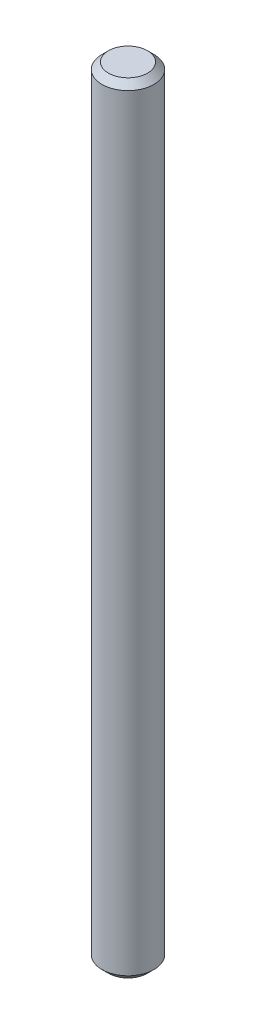
SolidWorks part; units mm, degrees
ref_plane "前基準面" through (0, 0, 0) normal (0, 0, 1) x (1, 0, 0)
ref_plane "上基準面" through (0, 0, 0) normal (0, 1, 0) x (1, 0, 0)
ref_plane "右基準面" through (0, 0, 0) normal (1, 0, 0) x (0, 0, -1)
sketch "草圖1" plane through (0, 0, 0) normal (0, 1, 0) x (1, 0, 0)
  circle A0 centre (0, 0) radius 4
  dimension "D1" = 8
extrude "填料-伸長1" add sketch "草圖1" along normal blind 120
chamfer "導角1" distance 1 angle 45 2 edges at (0, 0, 4) (0, 120, 4)
sketch "草圖2" plane through (0, 0, 0) normal (1, 0, 0) x (0, 0, -1)
  line L0 (0, 125.3912) -> (0, -9.0868) construction
